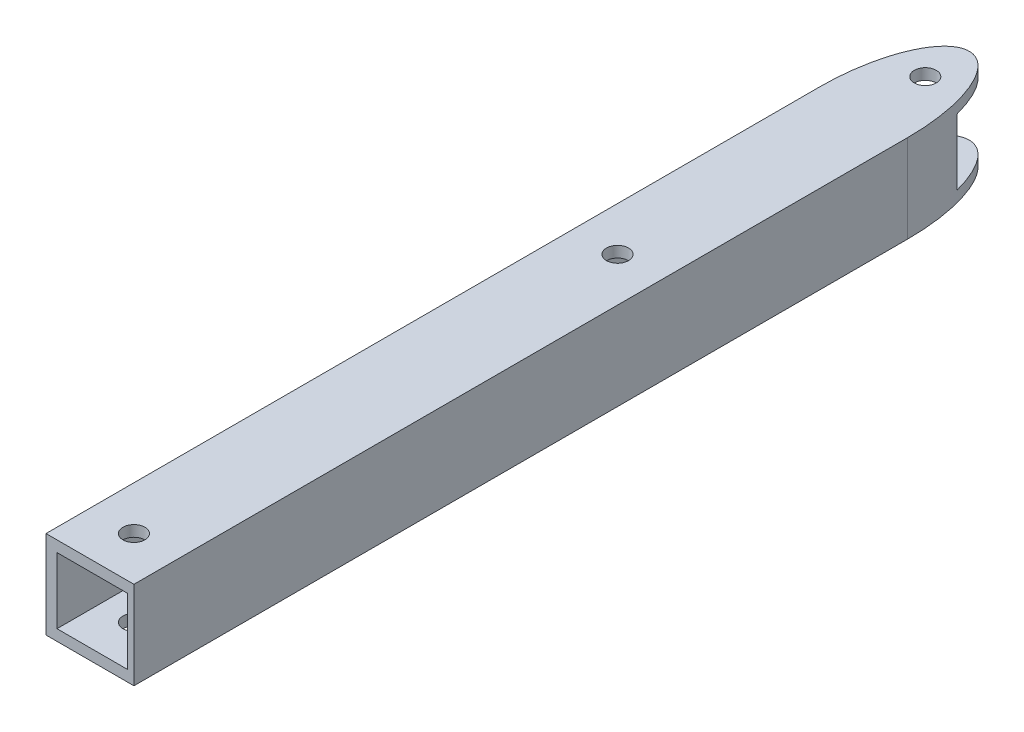
SolidWorks part; units mm, degrees
ref_plane "Front Plane" through (0, 0, 0) normal (0, 0, 1) x (1, 0, 0)
ref_plane "Top Plane" through (0, 0, 0) normal (0, 1, 0) x (1, 0, 0)
ref_plane "Right Plane" through (0, 0, 0) normal (1, 0, 0) x (0, 0, -1)
sketch "Sketch1" plane through (0, 0, 0) normal (0, 0, 1) x (1, 0, 0)
  line L1 (0, 0) -> (25.4, 0)
  line L2 (0, 0) -> (0, 25.4)
  line L3 (0, 25.4) -> (25.4, 25.4)
  line L4 (25.4, 0) -> (25.4, 25.4)
  dimension "D1" = 25.4
  dimension "D2" = 25.4
extrude "Boss-Extrude2" add sketch "Sketch1" along normal blind 254 contours L3 L4 L1 L2
sketch "Sketch2" plane through (0, 0, 0) normal (0, 0, -1) x (-1, 0, 0)
  line L0 (-23.4778, 22.225) -> (-3.175, 22.225)
  line L1 (-23.4778, 22.225) -> (-23.4778, 3.175)
  line L2 (-23.4778, 3.175) -> (-3.175, 3.175)
  line L3 (-3.175, 22.225) -> (-3.175, 3.175)
  line L4 (0, 0) -> (0, 25.4) construction
  line L5 (0, 0) -> (-25.4, 0) construction
  dimension "D1" = 3.175
  dimension "D2" = 3.175
extrude "Cut-Extrude1" cut sketch "Sketch2" against normal through all
sketch "Sketch3" plane through (0, 25.4, 0) normal (0, 1, 0) x (1, 0, 0)
  line L4 (0, 0) -> (25.4, 0) construction
  line L5 (12.7, 0) -> (25.4, 0)
  line L6 (25.4, 0) -> (25.4, -30.4659)
  line L7 (12.7, 0) -> (0, 0)
  line L8 (0, 0) -> (0, -30.4659)
  ellipse E0 centre (12.7, -30.4659) end of major axis (12.7, 0) minor radius 12.7 (25.4, -30.4659) -> (0, -30.4659) ccw
  line M2 (25.4, 0) -> (0, 0)
  line M3 (0, 0) -> (0, -254)
  line M5 (25.4, -254) -> (25.4, 0)
extrude "Cut-Extrude2" cut sketch "Sketch3" against normal through all contours E0 M2 M3 | E0 M5 M2
sketch "Sketch4" plane through (0, 25.4, 0) normal (0, 1, 0) x (1, 0, 0)
  line L0 (25.4, -254) -> (0, -254)
  circle A1 centre (12.7, -101.6) radius 3.175
  dimension "D3" = 6.35
  dimension "D4" = 152.4
sketch "Sketch6" plane through (0, 25.4, 0) normal (0, 1, 0) x (1, 0, 0)
  line L0 (0, 0) -> (25.4, 0)
  circle A0 centre (12.7, -12.7) radius 3.175
  circle A1 centre (12.7, -1206.5) radius 3.175
  point P7 (12.7, 0)
  dimension "D2" = 6.35
  dimension "D3" = 12.7
  dimension "D4" = 6.35
  dimension "D5" = 1206.5
  dimension "D1" = 25.4
extrude "Cut-Extrude5" cut sketch "Sketch6" against normal through all contours A0
extrude "Cut-Extrude6" cut sketch "Sketch4" against normal through all contours A1
sketch "Sketch7" plane through (0, 25.4, 0) normal (0, 1, 0) x (1, 0, 0)
  line L0 (0, -254) -> (25.4, -254) construction
  circle A0 centre (12.7, -241.3) radius 3.175
  point P4 (12.7, -254)
  dimension "D1" = 12.7
extrude "Cut-Extrude7" cut sketch "Sketch7" against normal through all
